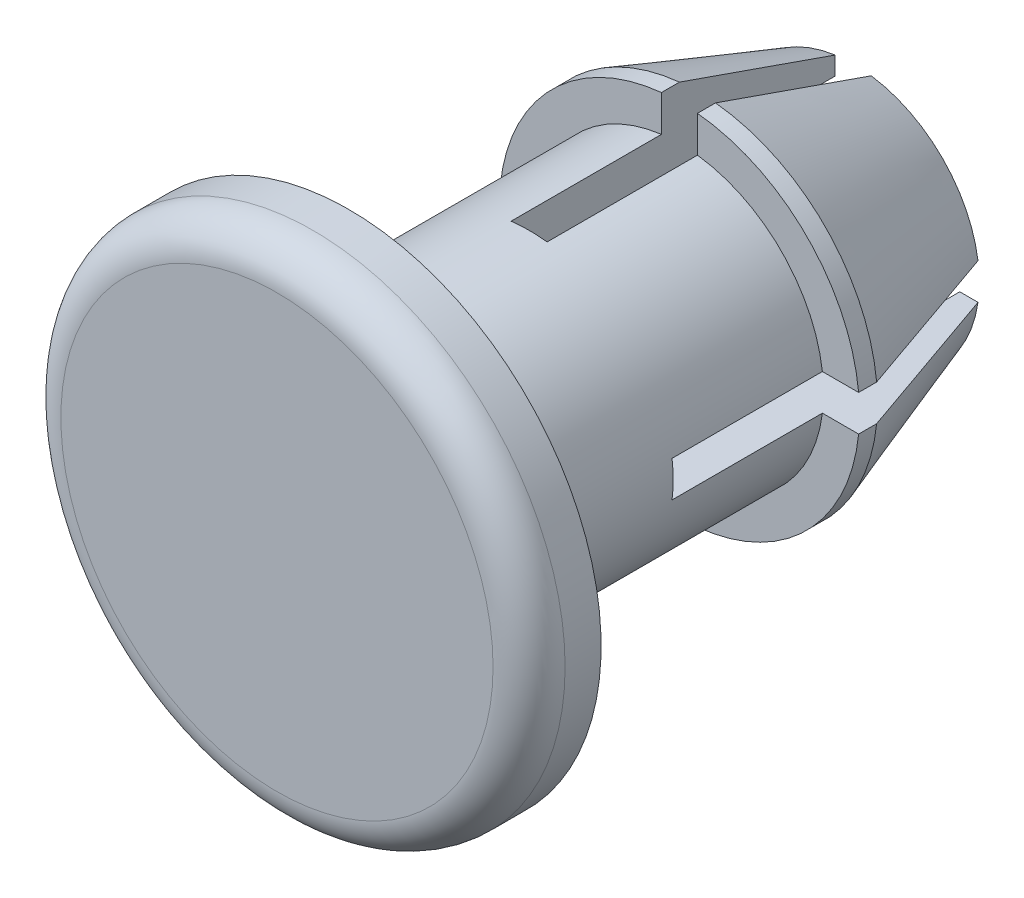
SolidWorks part; units mm, degrees
material "NYLATRON NSM"
ref_plane "Front" through (0, 0, 0) normal (0, 0, 1) x (1, 0, 0)
ref_plane "Top" through (0, 0, 0) normal (0, 1, 0) x (1, 0, 0)
ref_plane "Right" through (0, 0, 0) normal (1, 0, 0) x (0, 0, -1)
sketch "Sketch1" plane through (0, 0, 0) normal (0, 0, 1) x (1, 0, 0)
  circle A0 centre (0, 0) radius 7
  dimension "D1" = 14
extrude "Boss-Extrude1" add sketch "Sketch1" along normal mid plane 16
sketch "Sketch2" plane through (0, 0, -8) normal (0, 0, -1) x (-1, 0, 0)
  circle A0 centre (0, 0) radius 5
  dimension "D1" = 10
extrude "Cut-Extrude1" cut sketch "Sketch2" against normal blind 14 flip side to cut
sketch "Sketch3" plane through (0, 0, 0) normal (0, 1, 0) x (1, 0, 0)
  line L3 (7, -6) -> (-7, -6) construction
  line L4 (-5, 3.675) -> (-3.5, 8)
  line L5 (-13, 3.175) -> (-4, 3.175)
  line L7 (5, 8) -> (-5, 8) construction
  line L8 (-3.5, 8) -> (-5, 8)
  line L9 (-5, 8) -> (-5, 3.675)
  line L12 (-13, 3.175) -> (-13, -6)
  line L13 (-13, -6) -> (-4, -6)
  line L14 (-4, 3.175) -> (-4, -6)
  line L15 (0, -8.8) -> (0, 8.8) construction
  line L16 (-5, 8) -> (-5, -6) construction
  point P6 (-9.0767, 2.7356)
  point P13 (-7.9905, 7)
  point P15 (-8.2734, 4.9061)
  point P16 (-7.7076, 7)
  point P17 (-8, 5.22)
  point P20 (0, 0)
  point P21 (-8, 5.7514)
  point P22 (-4.9474, 8)
  point P23 (0, 0)
  dimension "D1" = 9
  dimension "D2" = 4
  dimension "D3" = 9.175
  dimension "D4" = 0.5
  dimension "D5" = 3.5
revolve "Cut-Revolve1" cut sketch "Sketch3" angle 360 about axis through (0, 0, 6) along (0, 0, -1)
sketch "Sketch4" plane through (0, 0, -8) normal (0, 0, -1) x (-1, 0, 0)
  circle A0 centre (0, 0) radius 3
  dimension "D1" = 6
extrude "Cut-Extrude2" cut sketch "Sketch4" against normal blind 15
sketch "Sketch5" plane through (0, 0, -8) normal (0, 0, -1) x (-1, 0, 0)
  line L0 (7.7, 0) -> (-7.7, 0) construction
  line L1 (-0.5, 12) -> (0.5, 12)
  line L2 (-0.5, 12) -> (-0.5, 0.5)
  line L3 (-0.5, -12) -> (0.5, -12)
  line L4 (0.5, 12) -> (0.5, 0.5)
  line L5 (-12, 0.5) -> (-0.5, 0.5)
  line L6 (-12, 0.5) -> (-12, -0.5)
  line L7 (-12, -0.5) -> (-0.5, -0.5)
  line L8 (12, 0.5) -> (12, -0.5)
  line L9 (0, 7.7) -> (0, -7.7) construction
  line L10 (-0.5, -0.5) -> (-0.5, -12)
  line L11 (0.5, -0.5) -> (12, -0.5)
  line L12 (0.5, -0.5) -> (0.5, -12)
  line L13 (0.5, 0.5) -> (12, 0.5)
  dimension "D1" = 1
  dimension "D2" = 0.5
  dimension "D3" = 1
  dimension "D4" = 0.5
  dimension "D5" = 24
  dimension "D6" = 12
  dimension "D7" = 24
  dimension "D8" = 12
extrude "Cut-Extrude3" cut sketch "Sketch5" against normal blind 9
fillet "Fillet1" radius 1 1 edges at (7, 0, 8)
